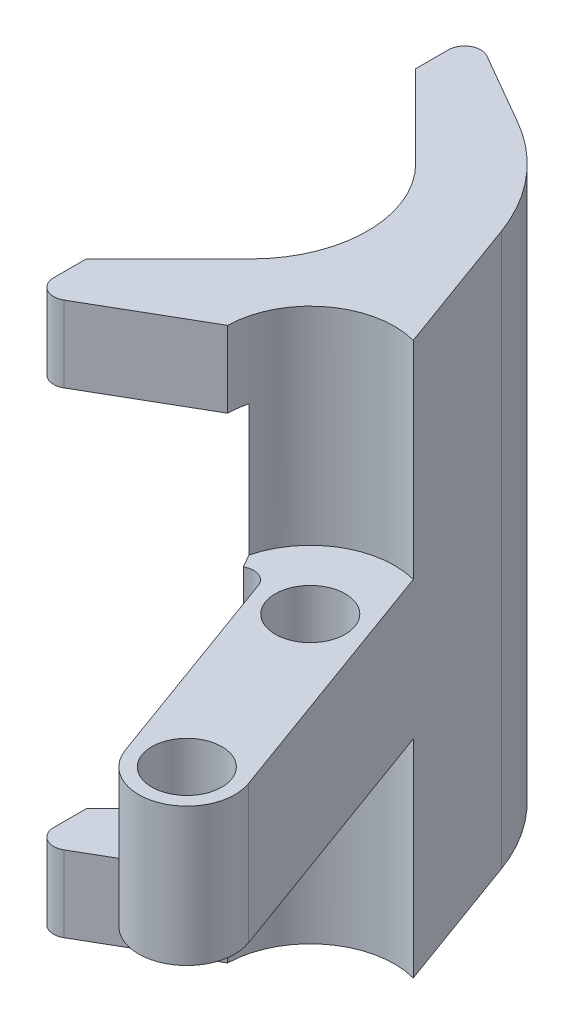
SolidWorks part; units mm, degrees
ref_plane "Front Plane" through (0, 0, 0) normal (0, 0, 1) x (1, 0, 0)
ref_plane "Top Plane" through (0, 0, 0) normal (0, 1, 0) x (1, 0, 0)
ref_plane "Right Plane" through (0, 0, 0) normal (1, 0, 0) x (0, 0, -1)
sketch "Sketch1" plane through (0, 0, 0) normal (0, 1, 0) x (1, 0, 0)
  line L0 (7.5771, 7.5771) -> (0, 15.1542)
  line L1 (7.5771, -7.5771) -> (0, -15.1542)
  line L2 (0, 0) -> (0, 8.6119) construction
  line L3 (0, 15.1542) -> (0, 18.1542)
  line L4 (2.25, 19.4532) -> (8.986, 15.5642)
  line L5 (16.8881, 6.1468) -> (30.2003, -30.4282)
  line L6 (0, -15.1542) -> (0, -18.1542)
  line L7 (2.25, -19.4532) -> (12.7152, -13.4111)
  line L8 (14.8747, -14.1971) -> (21.884, -33.455)
  line L9 (21.884, -33.455) -> (30.2003, -30.4282) construction
  line L10 (26.0422, -31.9416) -> (19.5438, -14.0874) construction
  line L11 (12.7152, -13.4111) -> (22.0459, -8.0241) construction
  circle A0 centre (0, 0) radius 10.7156 construction
  arc A1 (7.5771, 7.5771) -> (7.5771, -7.5771) centre (0, 0) cw
  arc A2 (0, 18.1542) -> (2.25, 19.4532) centre (1.5, 18.1542) cw
  arc A3 (8.986, 15.5642) -> (16.8881, 6.1468) centre (0, 0) cw
  arc A4 (0, -18.1542) -> (2.25, -19.4532) centre (1.5, -18.1542) ccw
  arc A5 (12.7152, -13.4111) -> (14.8747, -14.1971) centre (13.4652, -14.7102) cw
  arc A6 (21.884, -33.455) -> (30.2003, -30.4282) centre (26.0422, -31.9416) ccw
  circle A7 centre (26.0422, -31.9416) radius 3.225
  circle A8 centre (19.5438, -14.0874) radius 3.225
  dimension "D1" = 21.4312
  dimension "D4" = 1.5
  dimension "D7" = 1.5
  dimension "D9" = 4
  dimension "D10" = 1.2
  dimension "D11" = 6.45
  dimension "D12" = 1.5
  dimension "D2" = 45
  dimension "D3" = 15
  dimension "D5" = 3
  dimension "D6" = 20
  dimension "D8" = 15
  dimension "D13" = 19
extrude "Boss-Extrude1" add sketch "Sketch1" along normal blind 50.8
sketch "Sketch2" plane through (8.986, 0, 15.5642) normal (0.5, 0, 0.866) x (0.866, 0, -0.5)
  line L0 (-7.7781, 0) -> (4.3061, 0) construction
  line L1 (-7.7781, 50.8) -> (4.3061, 50.8) construction
  line L2 (-7.7781, 0) -> (4.3061, 0)
  line L3 (-7.7781, 50.8) -> (4.3061, 50.8) construction
  line L4 (-1.736, 50.8) -> (-1.736, 0) construction
  line L5 (-3.3239, 25.4) -> (27.4342, 25.4) construction
  line L6 (-128.736, 50.8) -> (125.264, 50.8)
  line L7 (-128.736, 31.75) -> (125.264, 31.75)
  line L8 (125.264, 31.75) -> (125.264, 50.8)
  line L9 (-128.736, 31.75) -> (-128.736, 50.8)
  line L10 (-128.736, 19.05) -> (125.264, 19.05)
  line L11 (125.264, 19.05) -> (125.264, 0)
  line L12 (-128.736, 0) -> (125.264, 0)
  line L13 (-128.736, 19.05) -> (-128.736, 0)
  point P7 (-1.736, 25.4)
  point P13 (-1.736, 50.8)
  dimension "D1" = 12.7
  dimension "D2" = 254
extrude "Cut-Extrude1" cut sketch "Sketch2" along normal through all contours L7 L8 L6 L9 | L12 L11 L10 L13
sketch "Sketch5" plane through (8.986, 0, 15.5642) normal (0.5, 0, 0.866) x (0.866, 0, -0.5)
  line L0 (4.3061, 7) -> (-7.7781, 7)
  line L1 (4.3061, 7) -> (4.3061, 43.8)
  line L2 (4.3061, 31.75) -> (4.3061, 19.05) construction
  line L6 (-7.7781, 50.8) -> (-7.7781, 0) construction
  line L7 (4.3061, 43.8) -> (-7.7781, 43.8)
  line L9 (-7.7781, 50.8) -> (15.0803, 50.8) construction
  line L10 (-7.7781, 0) -> (15.0803, 0) construction
  line L11 (-7.7781, 7) -> (-10.7781, 7)
  line L12 (-10.7781, 7) -> (-10.7781, 43.8)
  line L13 (-10.7781, 43.8) -> (-7.7781, 43.8)
  point P14 (3.6511, 0)
  dimension "D1" = 7
  dimension "D2" = 7
  dimension "D3" = 3
extrude "Cut-Extrude4" cut sketch "Sketch5" against normal blind 10
sketch "Sketch3" plane through (0, 31.75, 0) normal (0, 1, 0) x (1, 0, 0)
  circle A0 centre (19.5438, -14.0874) radius 7.75
  dimension "D1" = 15.5
extrude "Cut-Extrude2" cut sketch "Sketch3" along normal through all
sketch "Sketch4" plane through (0, 19.05, 0) normal (0, -1, 0) x (1, 0, 0)
  circle A0 centre (19.5438, 14.0874) radius 7.75
  dimension "D1" = 15.5
extrude "Cut-Extrude3" cut sketch "Sketch4" along normal through all
